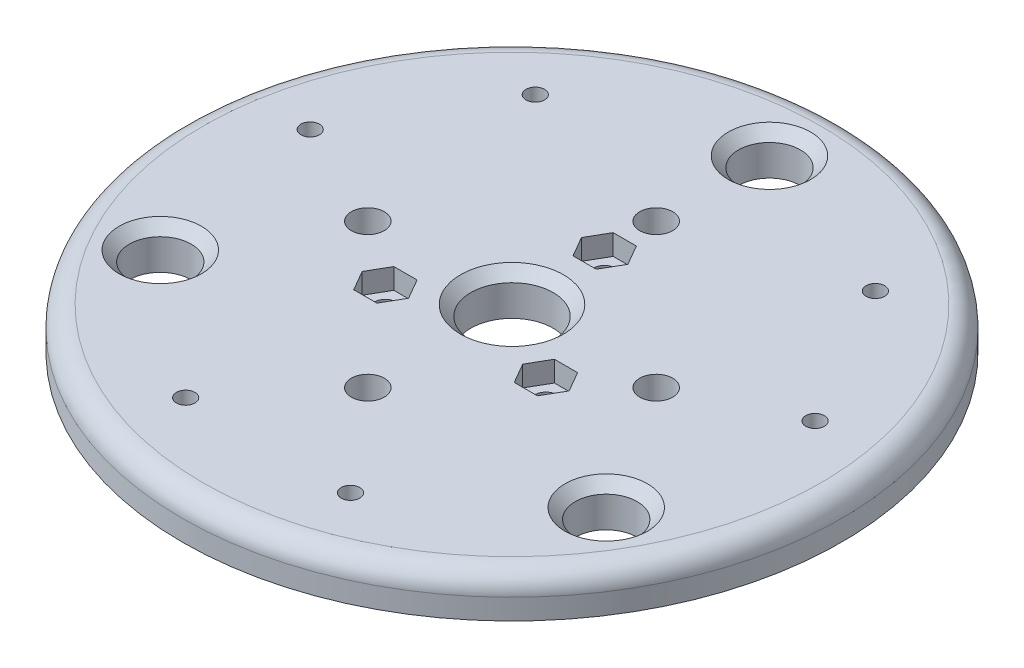
SolidWorks part; units mm, degrees
ref_plane "Спереди" through (0, 0, 0) normal (0, 0, 1) x (1, 0, 0)
ref_plane "Сверху" through (0, 0, 0) normal (0, 1, 0) x (1, 0, 0)
ref_plane "Справа" through (0, 0, 0) normal (1, 0, 0) x (0, 0, -1)
sketch "Эскиз1" plane through (0, 0, 0) normal (0, 1, 0) x (1, 0, 0)
  circle A3 centre (0, 0) radius 32
  circle A4 centre (0, 0) radius 4
  circle A6 centre (0, 0) radius 25 construction
  circle A7 centre (0, 25) radius 3
  circle A8 centre (21.6506, -12.5) radius 3
  circle A9 centre (-21.6506, -12.5) radius 3
  dimension "D4" = 64
  dimension "D1" = 8
  dimension "D2" = 50
  dimension "D3" = 6
  dimension "D5" = 3
extrude "Бобышка-Вытянуть1" add sketch "Эскиз1" along normal blind 4
fillet "Скругление1" radius 2 1 edges at (0, 4, 32)
sketch "Эскиз2" plane through (0, 4, 0) normal (0, 1, 0) x (1, 0, 0)
  circle A0 centre (0, 0) radius 9 construction
  circle A1 centre (0, 9) radius 1.1
  circle A2 centre (7.7942, -4.5) radius 1.1
  circle A3 centre (-7.7942, -4.5) radius 1.1
  dimension "D1" = 18
  dimension "D2" = 2.2
  dimension "D3" = 3
extrude "Вырез-Вытянуть1" cut sketch "Эскиз2" against normal through all
sketch "Эскиз3" plane through (0, 0, 0) normal (0, -1, 0) x (1, 0, 0)
  circle A0 centre (0, 0) radius 14 construction
  circle A1 centre (0, 14) radius 1.6
  circle A2 centre (14, 0) radius 1.6
  circle A3 centre (0, -14) radius 1.6
  circle A4 centre (-14, 0) radius 1.6
  dimension "D1" = 28
  dimension "D2" = 3.2
  dimension "D3" = 4
extrude "Вырез-Вытянуть2" cut sketch "Эскиз3" against normal through all
sketch "Эскиз4" plane through (0, 4, 0) normal (0, 1, 0) x (1, 0, 0)
  line L0 (5.5426, -4.5) -> (6.6684, -6.45)
  line L1 (1.1258, 7.05) -> (2.2517, 9)
  line L2 (2.2517, 9) -> (1.1258, 10.95)
  line L3 (1.1258, 10.95) -> (-1.1258, 10.95)
  line L4 (-1.1258, 10.95) -> (-2.2517, 9)
  line L5 (-2.2517, 9) -> (-1.1258, 7.05)
  line L6 (-1.1258, 7.05) -> (1.1258, 7.05)
  line L7 (6.6684, -6.45) -> (8.9201, -6.45)
  line L8 (8.9201, -6.45) -> (10.0459, -4.5)
  line L9 (10.0459, -4.5) -> (8.9201, -2.55)
  line L10 (8.9201, -2.55) -> (6.6684, -2.55)
  line L11 (6.6684, -2.55) -> (5.5426, -4.5)
  line L12 (-6.6684, -2.55) -> (-8.9201, -2.55)
  line L13 (-8.9201, -2.55) -> (-10.0459, -4.5)
  line L14 (-10.0459, -4.5) -> (-8.9201, -6.45)
  line L15 (-8.9201, -6.45) -> (-6.6684, -6.45)
  line L16 (-6.6684, -6.45) -> (-5.5426, -4.5)
  line L17 (-5.5426, -4.5) -> (-6.6684, -2.55)
  circle A0 centre (0, 9) radius 1.95 construction
  circle A1 centre (7.7942, -4.5) radius 1.95 construction
  circle A2 centre (-7.7942, -4.5) radius 1.95 construction
  circle A3 centre (7.7942, -4.5) radius 1.1 construction
  dimension "D1" = 3.9
  dimension "D2" = 3
extrude "Вырез-Вытянуть3" cut sketch "Эскиз4" against normal blind 2
chamfer "Фаска1" distance 1 angle 45 4 edges at (0, 4, -22) (21.6506, 4, 15.5) (-21.6506, 4, 15.5) (0, 4, 4)
sketch "Эскиз5" plane through (0, 4, 0) normal (0, 1, 0) x (1, 0, 0)
  line L0 (0, 0) -> (0, -25) construction
  line L1 (8, -23.6854) -> (-8, -23.6854) construction
  circle A0 centre (0, 0) radius 25 construction
  circle A1 centre (-8, -23.6854) radius 0.9
  circle A2 centre (8, -23.6854) radius 0.9
  circle A3 centre (-16.5122, 18.7709) radius 0.9
  circle A4 centre (-24.5122, 4.9145) radius 0.9
  circle A5 centre (24.5122, 4.9145) radius 0.9
  circle A6 centre (16.5122, 18.7709) radius 0.9
  dimension "D2" = 1.8
  dimension "D3" = 1.8
  dimension "D1" = 16
  dimension "D4" = 3
extrude "Вырез-Вытянуть4" cut sketch "Эскиз5" against normal through all
equation "\"motor_diameter\"= 30"
equation "\"mm_diameter\"= IIF ( \"motor_diameter\" < 34 , 41 , \"motor_diameter\" + 8 )"
equation "\"upper_shafts_diameter\"= 5"
equation "\"upper_shats_length\"= 180"
equation "\"upper_bearing_d1\"= 10"
equation "\"upper_bearing_d2\"= 5"
equation "\"upper_bearing_h\"= 15"
equation "\"lower_shafts_diameter\"= 5"
equation "\"lower_shafts_length\"= 180"
equation "\"lower_bearing_d1\"= 10"
equation "\"lower_bearing_d2\"= 5"
equation "\"lower_bearing_h\"= 15"
equation "\"print_offset\"= 0.2"
equation "\"bh_screws_d\"= 2"
equation "\"bh_screws_h\"= 20"
equation "\"bh_screws_hh_d\"= 3.4"
equation "\"bh_screws_hh_h\"= 2"
equation "\"bh_nut_d\"= 3.8"
equation "\"bh_nut_h\"= 2"
equation "\"motor_screws_d\"= 3"
equation "\"motor_screws_h\"= 16"
equation "\"motor_screws_hh_d\"= 5.5"
equation "\"motor_screws_hh_h\"= 3"
equation "\"plate_hole_distance\"= 25.4"
equation "\"plate_screws_d\"= 6.5"
equation "\"shafts_diameter\"= IIF ( \"mm_diameter\" < 42 , 42 + 8 , \"mm_diameter\" + 8 )"
equation "\"D4@Эскиз1\"= \"system_radius\" * 2"
equation "\"central_hole_diameter\"= 8"
equation "\"bh_thikness\"= 4"
equation "\"D1@Эскиз1\"=\"central_hole_diameter\""
equation "\"D2@Эскиз1\"=\"shafts_diameter\""
equation "\"D3@Эскиз1\"=\"upper_shafts_diameter\"+1"
equation "\"D1@Бобышка-Вытянуть1\"=\"bh_thikness\""
equation "\"D2@Эскиз2\"=\"bh_screws_d\"+\"print_offset\""
equation "\"D2@Эскиз3\"=\"motor_screws_d\"+\"print_offset\""
equation "\"D1@Эскиз4\"=\"bh_nut_d\"+\"print_offset\"/2"
equation "\"D1@Вырез-Вытянуть3\"=\"bh_nut_h\""
equation "\"D2@Эскиз5\"=\"bh_screws_d\"-\"print_offset\""
equation "\"D3@Эскиз5\"=\"D2@Эскиз5\""
equation "\"ends_screws_d\"= 4"
equation "\"ends_screws_h\"= 16"
equation "\"ends_screws_hh_d\"= 6.7"
equation "\"ends_screws_hh_h\"= 4.1"
equation "\"ends_nut_d\"= 6.8"
equation "\"ends_nut_h\"= 3"
equation "\"system_radius\" = ( \"shafts_diameter\" + 12 + \"bh_thikness\" / 2 ) / 2"
equation "\"encoder_distance\"= \"system_radius\" + 4"
equation "\"tape_position\"= \"encoder_distance\" - 2 + 3.9 + 1.7 / 2"
